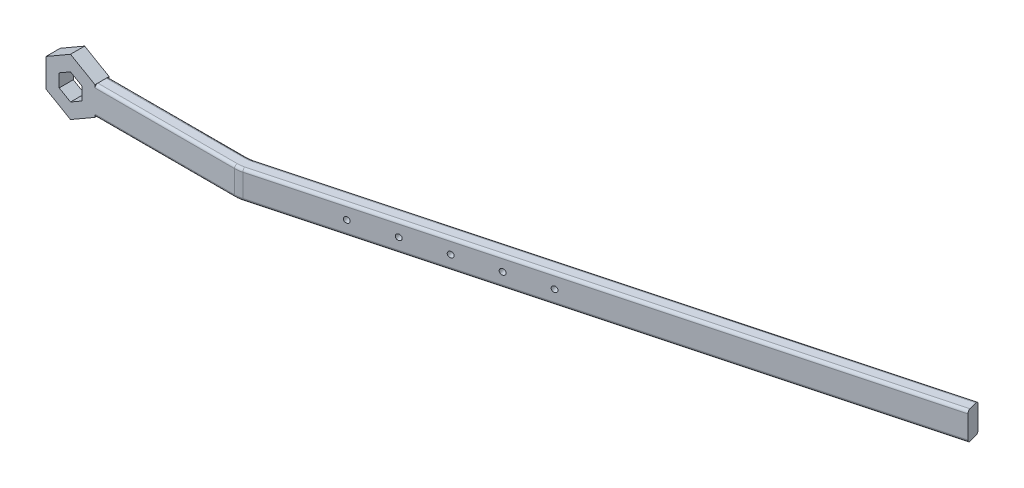
SolidWorks part; units mm, degrees
ref_plane "前视基准面" through (0, 0, 0) normal (0, 0, 1) x (1, 0, 0)
ref_plane "上视基准面" through (0, 0, 0) normal (0, 1, 0) x (1, 0, 0)
ref_plane "右视基准面" through (0, 0, 0) normal (1, 0, 0) x (0, 0, -1)
sketch "Sketch1" plane through (0, 0, 0) normal (0, 1, 0) x (1, 0, 0)
  line L0 (-50, 11.7953) -> (0, 11.7953)
  line L1 (0, 11.7953) -> (202.8444, 66.1473)
  line L2 (-50, 6.7953) -> (0.6583, 6.7953)
  line L3 (0.6583, 6.7953) -> (204.1385, 61.3176)
  line L4 (-50, 11.7953) -> (-50, 6.7953)
  line L5 (202.8444, 66.1473) -> (204.1385, 61.3176)
  dimension "D1" = 50
  dimension "D2" = 210
  dimension "D3" = 165
  dimension "D4" = 5
extrude "Boss-Extrude1" add sketch "Sketch1" along normal blind 10
fillet "Fillet1" radius 10 2 edges at (0, 5, -11.7953) (0.6583, 5, -6.7953)
fillet "Fillet2" radius 1 12 edges at (-25.6583, 0, -11.7953) (-0.0113, 0, -11.8808) (-25.6583, 10, -11.7953) (-0.0113, 10, -11.8808) (-25.3291, 0, -6.7953) (0.647, 0, -6.8808) (-25.3291, 10, -6.7953) (0.647, 10, -6.8808) (102.058, 0, -39.1416) (102.058, 10, -39.1416) (103.0342, 0, -34.2268) (103.0342, 10, -34.2268)
ref_plane "Plane1" through (0, 0, -6.7953) normal (0, 0, 1) x (1, 0, 0)
sketch "Sketch2" plane through (0, 0, -6.7953) normal (0, 0, 1) x (1, 0, 0)
  line L0 (-50, 10) -> (-50, 0)
  line L1 (-50, 0) -> (-50, 10)
  line L2 (-50, 10) -> (-58.6603, 15)
  line L3 (-58.6603, 15) -> (-67.3205, 10)
  line L4 (-67.3205, 10) -> (-67.3205, 0)
  line L5 (-67.3205, 0) -> (-58.6603, -5)
  line L6 (-58.6603, -5) -> (-50, 0)
  line L8 (-54.6603, 7.3094) -> (-58.6603, 9.6188)
  line L9 (-58.6603, 9.6188) -> (-62.6603, 7.3094)
  line L10 (-62.6603, 7.3094) -> (-62.6603, 2.6906)
  line L11 (-62.6603, 2.6906) -> (-58.6603, 0.3812)
  line L12 (-58.6603, 0.3812) -> (-54.6603, 2.6906)
  line L13 (-54.6603, 2.6906) -> (-54.6603, 7.3094)
  circle A0 centre (-58.6603, 5) radius 8.6603 construction
  circle A1 centre (-58.6603, 5) radius 4 construction
  dimension "D1" = 10
  dimension "D2" = 0
extrude "Boss-Extrude2" add sketch "Sketch2" against normal blind 5 contours L5 L6 L0 L2 L3 L4 L13 L12 L11 L10 L9 L8
sketch "Sketch3" plane through (-1.6547, 0, -6.1755) normal (0.2588, 0, 0.9659) x (0.9659, 0, -0.2588)
  circle A1 centre (33.7111, 5) radius 1
  circle A2 centre (48.7111, 5) radius 1
  circle A3 centre (63.7111, 5) radius 1
  circle A4 centre (78.7111, 5) radius 1
  circle A5 centre (93.7111, 5) radius 1
  dimension "D3" = 15
  dimension "D4" = 15
  dimension "D5" = 3
extrude "Cut-Extrude1" cut sketch "Sketch3" against normal up to next
